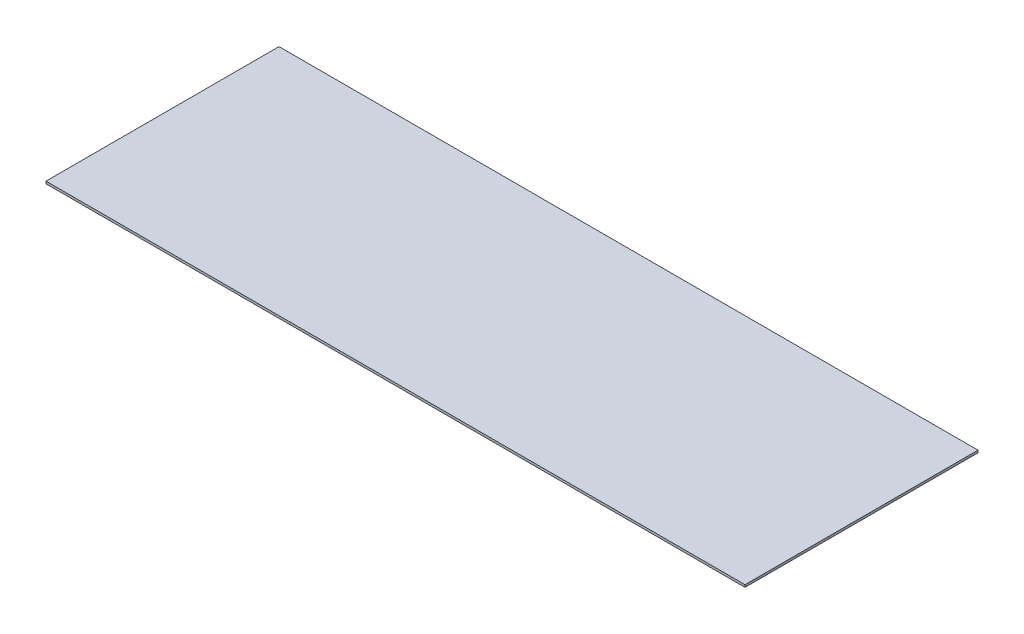
SolidWorks part; units mm, degrees
ref_plane "正面" through (0, 0, 0) normal (0, 0, 1) x (1, 0, 0)
ref_plane "平面" through (0, 0, 0) normal (0, 1, 0) x (1, 0, 0)
ref_plane "右側面" through (0, 0, 0) normal (1, 0, 0) x (0, 0, -1)
sketch "ｽｹｯﾁ1" plane through (0, 0, 0) normal (0, 1, 0) x (1, 0, 0)
  line L1 (0, 0) -> (300, 0)
  line L2 (0, 0) -> (0, 100)
  line L3 (0, 100) -> (300, 100)
  line L4 (300, 0) -> (300, 100)
  dimension "D1" = 100
  dimension "D2" = 300
extrude "ﾎﾞｽ - 押し出し1" add sketch "ｽｹｯﾁ1" along normal blind 1
